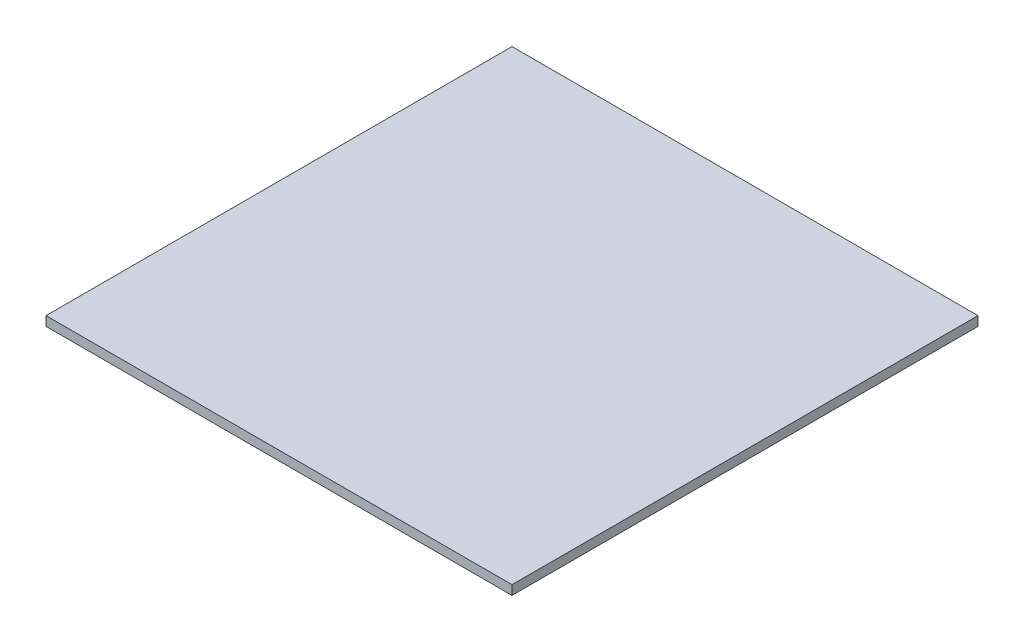
SolidWorks part; units mm, degrees
ref_plane "Front Plane" through (0, 0, 0) normal (0, 0, 1) x (1, 0, 0)
ref_plane "Top Plane" through (0, 0, 0) normal (0, 1, 0) x (1, 0, 0)
ref_plane "Right Plane" through (0, 0, 0) normal (1, 0, 0) x (0, 0, -1)
sketch "Sketch1" plane through (0, 0, 0) normal (0, 1, 0) x (1, 0, 0)
  line L1 (125, -125) -> (-125, -125)
  line L2 (125, -125) -> (125, 125)
  line L3 (125, 125) -> (-125, 125)
  line L4 (-125, -125) -> (-125, 125)
  line L5 (125, -125) -> (-125, 125) construction
  line L6 (125, 125) -> (-125, -125) construction
  point P1 (0, 0)
extrude "Boss-Extrude1" add sketch "Sketch1" along normal blind 5
sketch "Sketch2" plane through (0, 5, 0) normal (0, 1, 0) x (1, 0, 0)
  line L1 (-110, 110) -> (-95, 110)
  line L2 (-110, 110) -> (-110, 95)
  line L3 (-110, 95) -> (-95, 95)
  line L4 (-95, 110) -> (-95, 95)
  line L5 (-110, 110) -> (-95, 95) construction
  line L6 (-110, 95) -> (-95, 110) construction
  line L8 (0, 125) -> (0, -125)
  line L9 (-92.5, 92.5) -> (-112.5, 92.5)
  line L10 (-92.5, 92.5) -> (-92.5, 112.5)
  line L11 (-92.5, 112.5) -> (-112.5, 112.5)
  line L12 (-112.5, 92.5) -> (-112.5, 112.5)
  line L13 (-92.5, 92.5) -> (-112.5, 112.5) construction
  line L14 (-92.5, 112.5) -> (-112.5, 92.5) construction
  line L15 (125, 125) -> (-125, 125) construction
  line L16 (-125, -125) -> (125, -125) construction
  line L17 (-125.9646, 0) -> (125, 0)
  line L19 (125, -125) -> (125, 125) construction
  line L20 (92.5, 112.5) -> (112.5, 92.5) construction
  line L21 (92.5, 92.5) -> (112.5, 112.5) construction
  line L22 (110, 95) -> (95, 110) construction
  line L23 (110, 110) -> (95, 95) construction
  line L24 (112.5, 92.5) -> (112.5, 112.5)
  line L25 (92.5, 112.5) -> (112.5, 112.5)
  line L26 (92.5, 92.5) -> (92.5, 112.5)
  line L27 (92.5, 92.5) -> (112.5, 92.5)
  line L28 (95, 110) -> (95, 95)
  line L29 (110, 95) -> (95, 95)
  line L30 (110, 110) -> (110, 95)
  line L31 (110, 110) -> (95, 110)
  line L32 (-92.5, -112.5) -> (-112.5, -92.5) construction
  line L33 (-92.5, -92.5) -> (-112.5, -112.5) construction
  line L34 (-110, -95) -> (-95, -110) construction
  line L35 (-110, -110) -> (-95, -95) construction
  line L36 (-112.5, -92.5) -> (-112.5, -112.5)
  line L37 (-92.5, -112.5) -> (-112.5, -112.5)
  line L38 (-92.5, -92.5) -> (-92.5, -112.5)
  line L39 (-92.5, -92.5) -> (-112.5, -92.5)
  line L40 (-95, -110) -> (-95, -95)
  line L41 (-110, -95) -> (-95, -95)
  line L42 (-110, -110) -> (-110, -95)
  line L43 (-110, -110) -> (-95, -110)
  line L44 (110, -110) -> (95, -95) construction
  line L45 (110, -95) -> (95, -110) construction
  line L46 (92.5, -92.5) -> (112.5, -112.5) construction
  line L47 (92.5, -112.5) -> (112.5, -92.5) construction
  line L48 (110, -110) -> (95, -110)
  line L49 (110, -110) -> (110, -95)
  line L50 (110, -95) -> (95, -95)
  line L51 (95, -110) -> (95, -95)
  line L52 (92.5, -92.5) -> (112.5, -92.5)
  line L53 (92.5, -92.5) -> (92.5, -112.5)
  line L54 (92.5, -112.5) -> (112.5, -112.5)
  line L55 (112.5, -92.5) -> (112.5, -112.5)
  point P0 (-102.5, 102.5)
  point P9 (-102.5, 102.5)
  point P28 (102.5, 102.5)
  point P37 (-102.5, -102.5)
  point P46 (102.5, -102.5)
